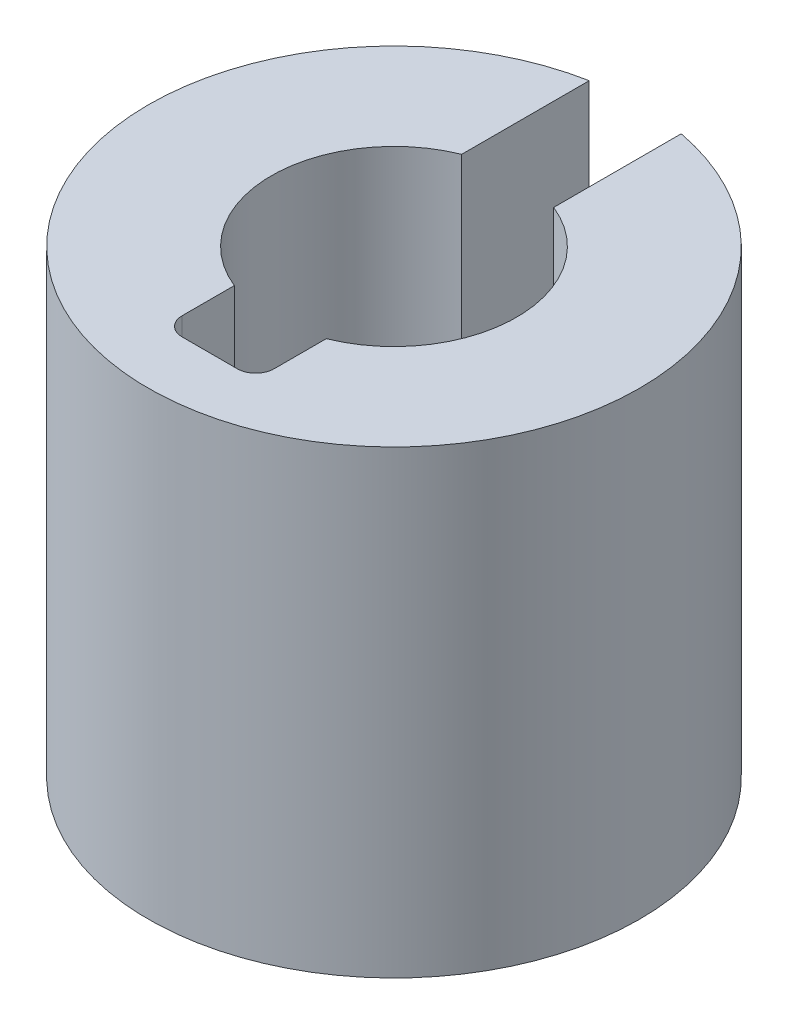
SolidWorks part; units mm, degrees
ref_plane "Front Plane" through (0, 0, 0) normal (0, 0, 1) x (1, 0, 0)
ref_plane "Top Plane" through (0, 0, 0) normal (0, 1, 0) x (1, 0, 0)
ref_plane "Right Plane" through (0, 0, 0) normal (1, 0, 0) x (0, 0, -1)
ref_plane "Plane1" through (0, -3.75, 0) normal (0, -1, 0) x (1, 0, 0)
sketch "Sketch1" plane through (0, -3.75, 0) normal (0, -1, 0) x (1, 0, 0)
  line L0 (0.75, -1.854) -> (0.75, -3.9341)
  line L1 (-0.75, -3.9341) -> (-0.75, -1.854)
  line L2 (-0.75, 1.854) -> (-0.75, 2.705)
  line L3 (-0.45, 3.005) -> (0.45, 3.005)
  line L4 (0.75, 2.705) -> (0.75, 1.854)
  arc A0 (0.75, -3.9341) -> (-0.75, -3.9341) centre (0, 0) ccw
  arc A1 (-0.75, -1.854) -> (-0.75, 1.854) centre (0, 0) cw
  arc A2 (-0.75, 2.705) -> (-0.45, 3.005) centre (-0.45, 2.705) cw
  arc A3 (0.45, 3.005) -> (0.75, 2.705) centre (0.45, 2.705) cw
  arc A4 (0.75, 1.854) -> (0.75, -1.854) centre (0, 0) cw
extrude "Boss-Extrude1" add sketch "Sketch1" against normal blind 7.5
